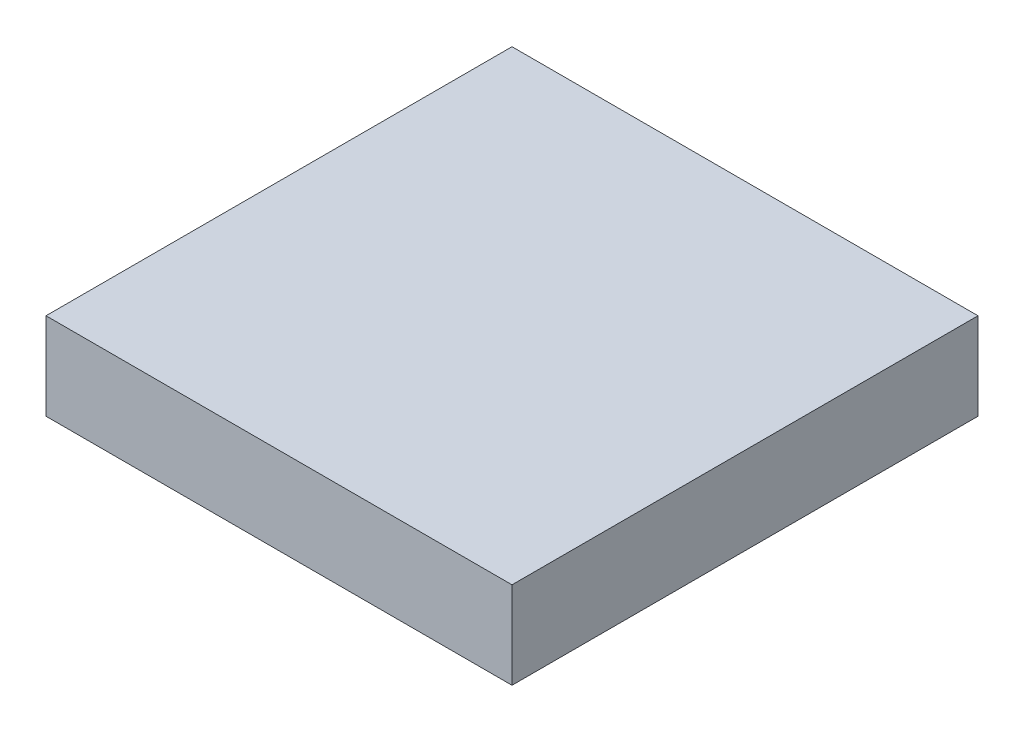
SolidWorks part; units mm, degrees
material "Acrylic (Medium-high impact)"
ref_plane "Front Plane" through (0, 0, 0) normal (0, 0, 1) x (1, 0, 0)
ref_plane "Top Plane" through (0, 0, 0) normal (0, 1, 0) x (1, 0, 0)
ref_plane "Right Plane" through (0, 0, 0) normal (1, 0, 0) x (0, 0, -1)
sketch "Sketch1" plane through (0, 0, 0) normal (0, 1, 0) x (1, 0, 0)
  line L1 (-8.5, 8.5) -> (8.5, 8.5)
  line L2 (-8.5, 8.5) -> (-8.5, -8.5)
  line L3 (-8.5, -8.5) -> (8.5, -8.5)
  line L4 (8.5, 8.5) -> (8.5, -8.5)
  line L5 (-8.5, 8.5) -> (8.5, -8.5) construction
  line L6 (-8.5, -8.5) -> (8.5, 8.5) construction
  point P0 (0, 0)
  dimension "D1" = 17
extrude "Boss-Extrude1" add sketch "Sketch1" along normal blind 3.175
